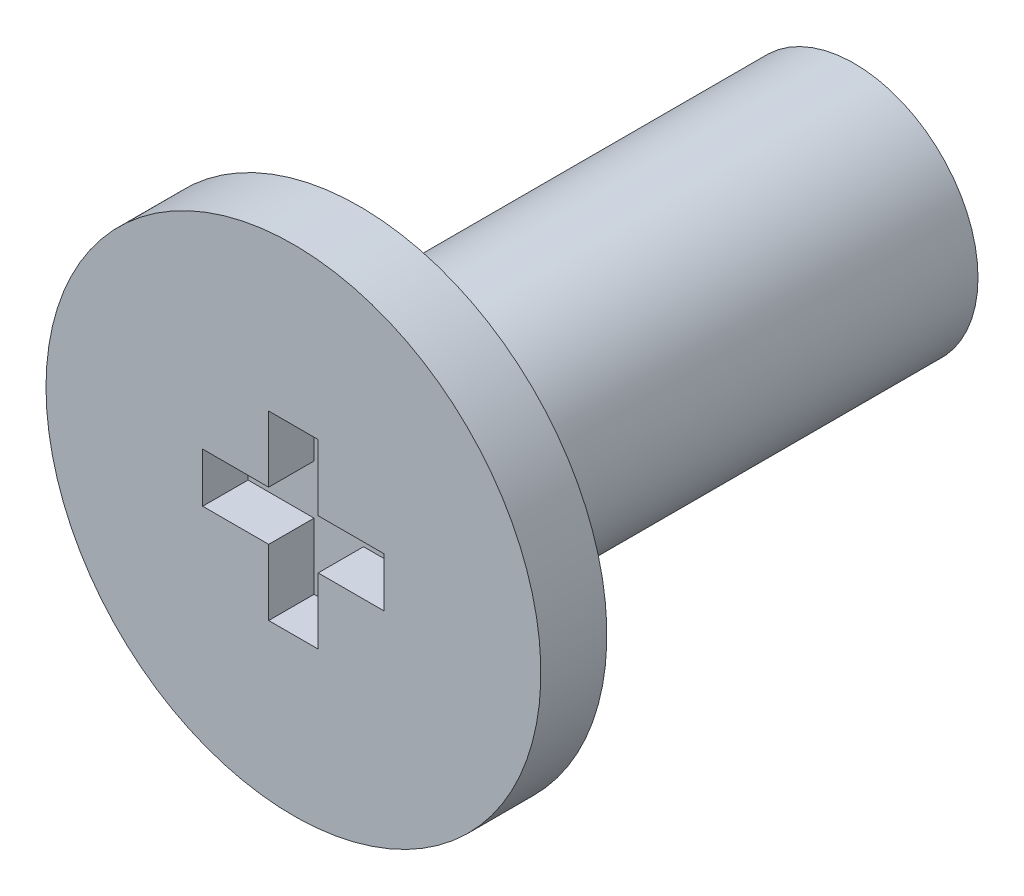
SolidWorks part; units mm, degrees
ref_plane "前视基准面" through (0, 0, 0) normal (0, 0, 1) x (1, 0, 0)
ref_plane "上视基准面" through (0, 0, 0) normal (0, 1, 0) x (1, 0, 0)
ref_plane "右视基准面" through (0, 0, 0) normal (1, 0, 0) x (0, 0, -1)
other "Configuration Table"
sketch "草图1" plane through (0, 0, 0) normal (0, 0, 1) x (1, 0, 0)
  circle A0 centre (0, 0) radius 1.5
extrude "标准杆径_头下长度" add sketch "草图1" against normal blind 6
sketch "草图2" plane through (0, 0, 0) normal (0, 0, 1) x (1, 0, 0)
  circle A0 centre (0, 0) radius 2.75
sketch "草图4" plane through (0, 0, 0) normal (0, 1, 0) x (1, 0, 0)
  line L0 (0, 0) -> (3.45, 0)
  line L1 (3.45, 0) -> (3.45, -0.3426)
  line L2 (0, -1.9) -> (0, 0)
  line L3 (0, 2) -> (0, -3.9) construction
  arc A0 (3.45, -0.3426) -> (0, -1.9) centre (0, 2.7) cw
sketch "草图5" plane through (0, 0, 0) normal (0, 0, 1) x (1, 0, 0)
  line L0 (-0.3, -1.45) -> (0.3, -1.45)
  line L1 (0.3, -1.45) -> (0.3, -0.3)
  line L2 (0.3, -0.3) -> (1.45, -0.3)
  line L3 (1.45, -0.3) -> (1.45, 0.3)
  line L4 (1.45, 0.3) -> (0.3, 0.3)
  line L5 (0.3, 0.3) -> (0.3, 1.45)
  line L6 (0.3, 1.45) -> (-0.3, 1.45)
  line L7 (-0.3, 1.45) -> (-0.3, 0.3)
  line L8 (-0.3, 0.3) -> (-1.45, 0.3)
  line L9 (-1.45, 0.3) -> (-1.45, -0.3)
  line L10 (-1.45, -0.3) -> (-0.3, -0.3)
  line L11 (-0.3, -0.3) -> (-0.3, -1.45)
sketch "草图6" plane through (0, 0, 0) normal (0, 1, 0) x (1, 0, 0)
  line L0 (0, 0) -> (3, 0)
  line L1 (3, 0) -> (3, -0.8)
  line L2 (3, -0.8) -> (0, -0.8)
  line L3 (0, -0.8) -> (0, 0)
  line L4 (0, 2) -> (0, -2.8) construction
revolve "已确认_十字槽超薄头" add sketch "草图6" angle 360 about L4
sketch "草图7" plane through (0, 0, 0) normal (0, 0, 1) x (1, 0, 0)
  line L0 (-0.3, -1.1) -> (0.3, -1.1)
  line L1 (0.3, -1.1) -> (0.3, -0.3)
  line L2 (0.3, -0.3) -> (1.1, -0.3)
  line L3 (1.1, -0.3) -> (1.1, 0.3)
  line L4 (1.1, 0.3) -> (0.3, 0.3)
  line L5 (0.3, 0.3) -> (0.3, 1.1)
  line L6 (0.3, 1.1) -> (-0.3, 1.1)
  line L7 (-0.3, 1.1) -> (-0.3, 0.3)
  line L8 (-0.3, 0.3) -> (-1.1, 0.3)
  line L9 (-1.1, 0.3) -> (-1.1, -0.3)
  line L10 (-1.1, -0.3) -> (-0.3, -0.3)
  line L11 (-0.3, -0.3) -> (-0.3, -1.1)
extrude "十字槽_PH1_简化" cut sketch "草图7" against normal blind 0.56 from offset 0.81
